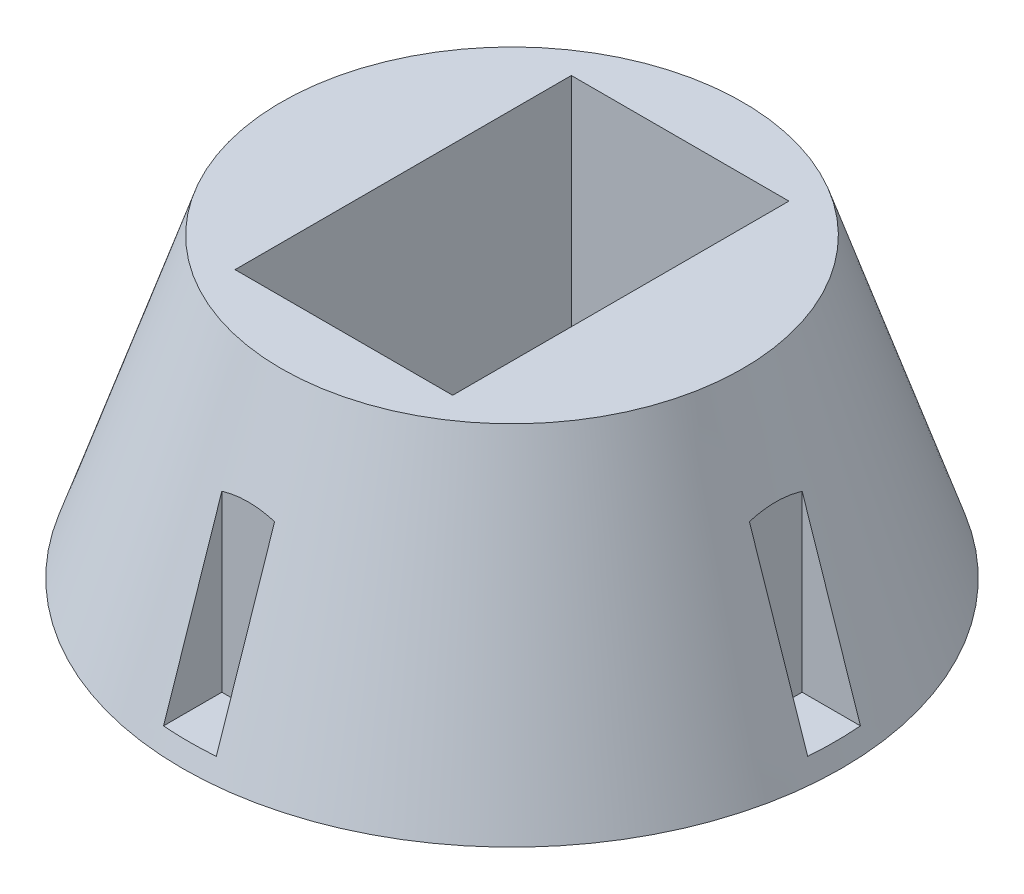
SolidWorks part; units mm, degrees
ref_plane "Plan de face" through (0, 0, 0) normal (0, 0, 1) x (1, 0, 0)
ref_plane "Plan de dessus" through (0, 0, 0) normal (0, 1, 0) x (1, 0, 0)
ref_plane "Plan de droite" through (0, 0, 0) normal (1, 0, 0) x (0, 0, -1)
sketch "Esquisse1" plane through (0, 0, 0) normal (0, 0, 1) x (1, 0, 0)
  line L0 (0, 185.6249) -> (0, -69.8928) construction
  line L1 (0, 0) -> (-50, 0)
  line L2 (-50, 0) -> (-35, 45)
  line L3 (-35, 45) -> (0, 45)
  line L4 (0, 45) -> (0, 0)
  dimension "D1" = 70
  dimension "D2" = 100
  dimension "D3" = 45
revolve "Révolution1" add sketch "Esquisse1" angle 360 about L0
sketch "Esquisse2" plane through (0, 45, 0) normal (0, 1, 0) x (1, 0, 0)
  line L0 (0, 36.703) -> (0, -41.6533) construction
  line L2 (16.5, -25.5) -> (-16.5, -25.5)
  line L3 (16.5, -25.5) -> (16.5, 25.5)
  line L4 (16.5, 25.5) -> (-16.5, 25.5)
  line L5 (-16.5, -25.5) -> (-16.5, 25.5)
  line L6 (16.5, -25.5) -> (-16.5, 25.5) construction
  line L7 (16.5, 25.5) -> (-16.5, -25.5) construction
  point P3 (0, 0)
  dimension "D1" = 33
  dimension "D2" = 51
extrude "Enlèv. mat.-Extru.1" cut sketch "Esquisse2" against normal blind 41
sketch "Esquisse3" plane through (0, 45, 0) normal (0, 1, 0) x (1, 0, 0)
  line L0 (0, -70.9025) -> (0, 59.7007) construction
  line L1 (-119.6559, 0) -> (92.9243, 0) construction
  line L7 (4, -52) -> (-4, -40) construction
  line L8 (4, 40) -> (-4, 40)
  line L18 (4, 40) -> (4, 52)
  line L19 (4, 52) -> (-4, 52)
  line L24 (-4, 40) -> (-4, 52)
  line L25 (4, 40) -> (-4, 52) construction
  line L26 (4, 52) -> (-4, 40) construction
  line L27 (52, -4) -> (40, -4)
  line L28 (52, -4) -> (52, 4)
  line L29 (52, 4) -> (40, 4)
  line L30 (40, -4) -> (40, 4)
  line L31 (52, -4) -> (40, 4) construction
  line L32 (52, 4) -> (40, -4) construction
  line L33 (4, -40) -> (-4, -52) construction
  line L34 (-4, -40) -> (-4, -52)
  line L35 (4, -52) -> (-4, -52)
  line L36 (4, -40) -> (4, -52)
  line L37 (4, -40) -> (-4, -40)
  line L38 (-52, 4) -> (-40, -4) construction
  line L39 (-52, -4) -> (-40, 4) construction
  line L40 (-40, -4) -> (-40, 4)
  line L41 (-52, 4) -> (-40, 4)
  line L42 (-52, -4) -> (-52, 4)
  line L43 (-52, -4) -> (-40, -4)
  point P4 (0, 46)
  point P5 (0, 0)
  point P10 (46, 0)
  point P19 (0, -46)
  point P24 (-46, 0)
  dimension "D1" = 12
  dimension "D2" = 8
  dimension "D4" = 40
  dimension "D3" = 40
  dimension "D5" = 8
  dimension "D6" = 12
extrude "Enlèv. mat.-Extru.3" cut sketch "Esquisse3" against normal blind 42
sketch "Esquisse4" plane through (0, 4, 0) normal (0, 1, 0) x (1, 0, 0)
  line L0 (0, 0) -> (19.3632, 0) construction
  line L1 (-12.7883, 6.6586) -> (10.7361, 6.6586)
  line L2 (-12.7883, 6.6586) -> (-12.7883, -7.9143)
  line L3 (-12.7883, -7.9143) -> (10.7361, -7.9143)
  line L4 (10.7361, 6.6586) -> (10.7361, -7.9143)
  dimension "D1" = 13.3172
  dimension "D2" = 10.7361
extrude "Enlèv. mat.-Extru.4" cut sketch "Esquisse4" against normal blind 269
sketch "Esquisse5" plane through (-405.4971, 45, -47.5357) normal (0, -1, 0) x (1, 0, 0)
  line L0 (405.4971, 73.0357) -> (405.4971, 47.6514) construction
  line L1 (388.9971, 73.0357) -> (421.9971, 73.0357) construction
  line L2 (405.4971, 47.6514) -> (308.8547, 206.8515) construction
sketch "Esquisse6" plane through (0, 3, 0) normal (0, 1, 0) x (1, 0, 0)
  circle A0 centre (0, 44.4607) radius 2.0856
  dimension "D1" = 4.1712
extrude "Enlèv. mat.-Extru.5" cut sketch "Esquisse6" against normal blind 10
